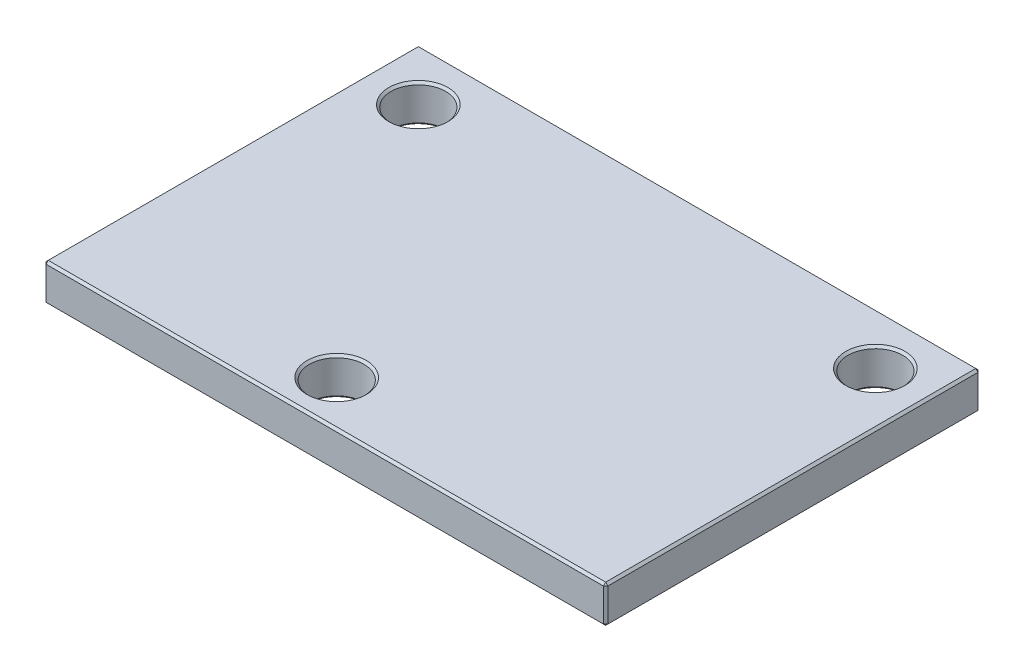
SolidWorks part; units mm, degrees
material "Plain Carbon Steel"
ref_plane "Front Plane" through (0, 0, 0) normal (0, 0, 1) x (1, 0, 0)
ref_plane "Top Plane" through (0, 0, 0) normal (0, 1, 0) x (1, 0, 0)
ref_plane "Right Plane" through (0, 0, 0) normal (1, 0, 0) x (0, 0, -1)
sketch "Sketch1" plane through (0, 0, 0) normal (0, 1, 0) x (1, 0, 0)
  line L1 (-375, -250) -> (375, -250)
  line L2 (-375, -250) -> (-375, 250)
  line L3 (-375, 250) -> (375, 250)
  line L4 (375, -250) -> (375, 250)
  line L5 (-375, -250) -> (375, 250) construction
  line L6 (-375, 250) -> (375, -250) construction
  point P0 (0, 0)
  dimension "D1" = 750
  dimension "D2" = 500
extrude "Boss-Extrude1" add sketch "Sketch1" against normal blind 50
sketch "Sketch2" plane through (0, 0, 0) normal (0, 1, 0) x (1, 0, 0)
  line L0 (375, 250) -> (-375, 250) construction
  line L1 (-375, 250) -> (-375, -250) construction
  line L2 (375, -250) -> (375, 250) construction
  line L3 (-375, -250) -> (375, -250) construction
  circle A0 centre (-305, 180) radius 36.5
  circle A1 centre (305, 180) radius 36.5
  circle A2 centre (-44, -190) radius 36.5
  dimension "D1" = 73
  dimension "D2" = 70
  dimension "D3" = 70
  dimension "D4" = 70
  dimension "D5" = 60
  dimension "D6" = 44
extrude "Cut-Extrude1" cut sketch "Sketch2" against normal up to next
chamfer "Chamfer1" distance 3 angle 45 6 edges at (305, -50, -216.5) (305, 0, -143.5) (-305, -50, -216.5) (-305, 0, -143.5) (-44, -50, 153.5) (-44, 0, 226.5)
chamfer "Chamfer2" distance 3 angle 45 12 edges at (-375, -25, -250) (-375, -25, 250) (375, -25, -250) (0, -50, -250) (-375, -50, 0) (0, -50, 250) (375, -50, 0) (375, -25, 250) (375, 0, 0) (0, 0, -250) (-375, 0, 0) (0, 0, 250)
